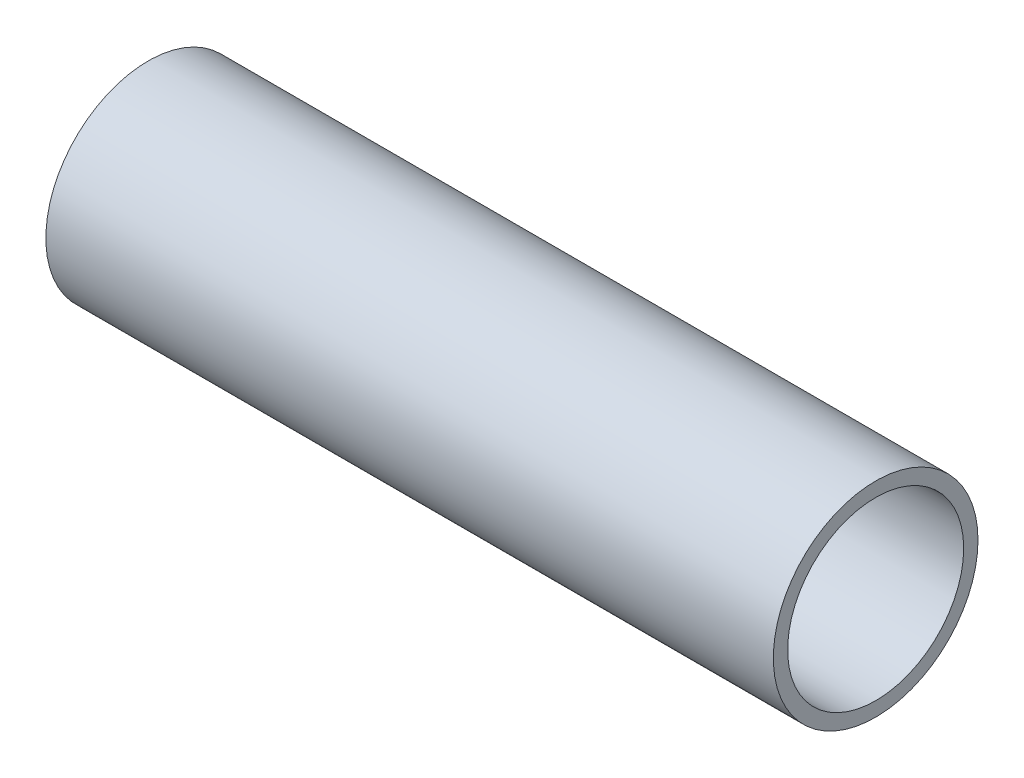
SolidWorks part; units mm, degrees
material "ASTM A106"
ref_plane "Front Plane" through (0, 0, 0) normal (0, 0, 1) x (1, 0, 0)
ref_plane "Top Plane" through (0, 0, 0) normal (0, 1, 0) x (1, 0, 0)
ref_plane "Right Plane" through (0, 0, 0) normal (1, 0, 0) x (0, 0, -1)
sketch "Sketch1" plane through (0, 0, 0) normal (1, 0, 0) x (0, 0, -1)
  circle A0 centre (0, 0) radius 21.1
  circle A1 centre (0, 0) radius 18.15
  dimension "D1" = 42.2
  dimension "D2" = 36.3
extrude "Boss-Extrude1" add sketch "Sketch1" along normal blind 150
